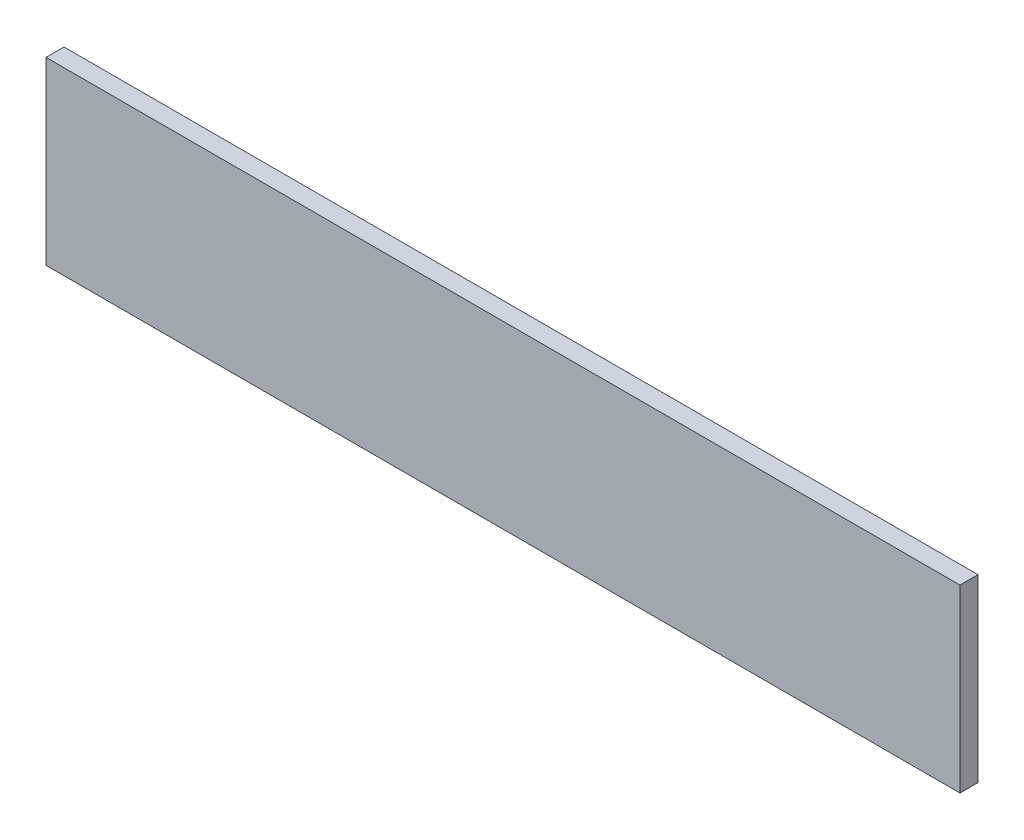
SolidWorks part; units mm, degrees
material "Простая углеродистая сталь"
ref_plane "Спереди" through (0, 0, 0) normal (0, 0, 1) x (1, 0, 0)
ref_plane "Сверху" through (0, 0, 0) normal (0, 1, 0) x (1, 0, 0)
ref_plane "Справа" through (0, 0, 0) normal (1, 0, 0) x (0, 0, -1)
sketch "Эскиз1" plane through (0, 0, 0) normal (0, 0, 1) x (1, 0, 0)
  line L1 (0, 0) -> (5075, 0)
  line L2 (0, 0) -> (0, -1000)
  line L3 (0, -1000) -> (5075, -1000)
  line L4 (5075, 0) -> (5075, -1000)
  line L5 (2537.5, -1000) -> (2537.5, 0) construction
  line L6 (0, -500) -> (5075, -500) construction
  point P88 (2537.5, -500)
  dimension "D1" = 5075
  dimension "D2" = 1000
extrude "Бобышка-Вытянуть1" add sketch "Эскиз1" along normal blind 100
